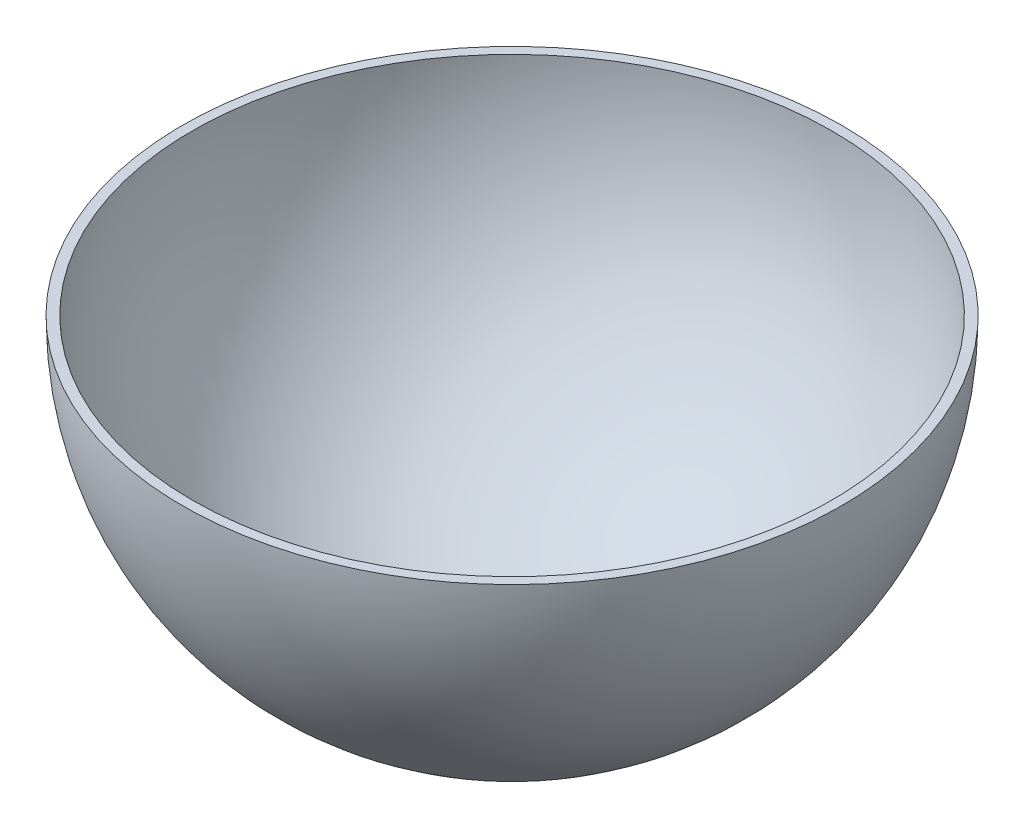
SolidWorks part; units mm, degrees
ref_plane "Front Plane" through (0, 0, 0) normal (0, 0, 1) x (1, 0, 0)
ref_plane "Top Plane" through (0, 0, 0) normal (0, 1, 0) x (1, 0, 0)
ref_plane "Right Plane" through (0, 0, 0) normal (1, 0, 0) x (0, 0, -1)
sketch "Sketch1" plane through (0, 0, 0) normal (0, 1, 0) x (1, 0, 0)
  line L0 (-90.1536, 0) -> (98.6, 0) construction
  line L1 (-55.6325, 0) -> (55.6325, 0) construction
  line L2 (-101.6, 0) -> (-98.6, 0)
  line L3 (98.6, 0) -> (101.6, 0)
  arc A0 (-101.6, 0) -> (101.6, 0) centre (0, 0) ccw
  arc A1 (98.6, 0) -> (-98.6, 0) centre (0, 0) cw
  dimension "D1" = 101.6
  dimension "D2" = 3
revolve "Revolve5" add sketch "Sketch1" angle 180 about L0
